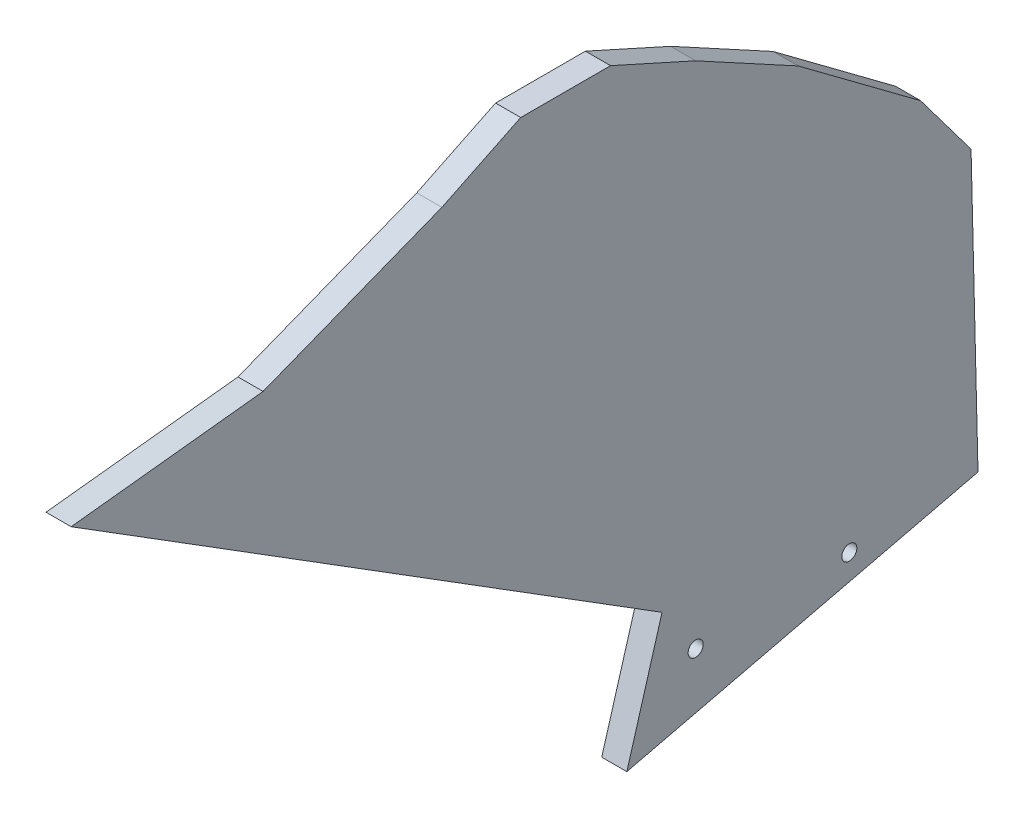
SolidWorks part; units mm, degrees
ref_plane "前视基准面" through (0, 0, 0) normal (0, 0, 1) x (1, 0, 0)
ref_plane "上视基准面" through (0, 0, 0) normal (0, 1, 0) x (1, 0, 0)
ref_plane "右视基准面" through (0, 0, 0) normal (1, 0, 0) x (0, 0, -1)
other "Configuration Table"
sketch "草图1" plane through (0, 0, 0) normal (1, 0, 0) x (0, 0, -1)
  line L14 (-5.4837, -5.7462) -> (22.4869, 0.9392)
  line L15 (-5.4837, -5.7462) -> (-2.6784, 3.8426)
  line L16 (-2.6784, 3.8426) -> (-49.7454, 33.2816)
  line L17 (-49.7454, 33.2816) -> (-34.4555, 34.9687)
  line L19 (17.9147, 28.8392) -> (21.9345, 23.4859)
  line L20 (21.9345, 23.4859) -> (22.4869, 0.9392)
  line L21 (17.9147, 28.8392) -> (8.1584, 36.1151)
  line L22 (8.1584, 36.1151) -> (0, 40.5466)
  line L23 (0, 40.5466) -> (-6.7809, 43.6026)
  line L24 (-6.7809, 43.6026) -> (-13.9361, 43.6026)
  line L25 (-13.9361, 43.6026) -> (-20.2109, 40.5466)
  line L26 (-20.2109, 40.5466) -> (-34.4555, 34.9687)
  circle A0 centre (0, 0) radius 0.6
  circle A1 centre (12.2371, 0.5185) radius 0.6
  dimension "D1" = 1.2
  dimension "D5" = 1.2
extrude "凸台-拉伸1" add sketch "草图1" along normal blind 2
